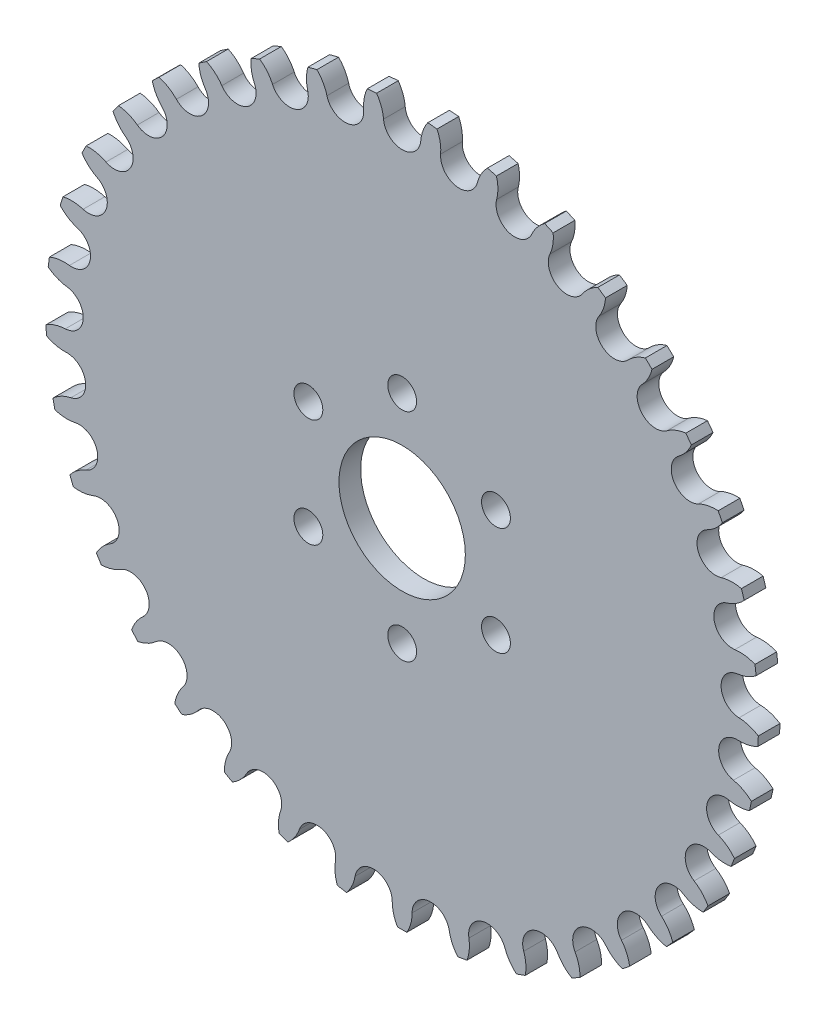
SolidWorks part; units mm, degrees
material "AISI 1020"
ref_plane "Спереди" through (0, 0, 0) normal (0, 0, 1) x (1, 0, 0)
ref_plane "Сверху" through (0, 0, 0) normal (0, 1, 0) x (1, 0, 0)
ref_plane "Справа" through (0, 0, 0) normal (1, 0, 0) x (0, 0, -1)
sketch "Эскиз1" plane through (0, 0, 0) normal (0, 0, 1) x (1, 0, 0)
  line L0 (0, 0) -> (0, 85) construction
  line L1 (0, 85) -> (15.8056, 83.5176) construction
  line L2 (15.8056, 83.5176) -> (0, 0) construction
  line L3 (15.8056, 83.5176) -> (49.3989, 83.5176)
  line L4 (0, 0) -> (0, 93.5961)
  line L5 (0, 93.5961) -> (15.8178, 92.2498)
  line L6 (15.8178, 92.2498) -> (0, 0)
  circle A0 centre (0, 0) radius 85 construction
  circle A1 centre (0, 93.5961) radius 5.08
  circle A2 centre (15.8178, 92.2498) radius 5.08
  dimension "D1" = 170
  dimension "D6" = 10.16
  dimension "D2" = 15.875
  dimension "D3" = 10.716
  dimension "D4" = 33.5932
  dimension "D5" = 9.73
sketch "Эскиз2" plane through (0, 0, 0) normal (0, 0, 1) x (1, 0, 0)
  line L0 (0, 0) -> (0, 88.4161)
  line L1 (0, 0) -> (14.9424, 87.1443)
  line L4 (15.8178, 92.2498) -> (0, 0) construction
  arc A0 (10.6565, 92.6891) -> (9.652, 98.2029) centre (0, 93.5961) ccw
  arc A1 (0, 98.6761) -> (16.6763, 97.2567) centre (0, 0) cw construction
  circle A2 centre (0, 93.5961) radius 5.08 construction
  circle A3 centre (15.8178, 92.2498) radius 5.08 construction
  circle A4 centre (0, 0) radius 85 construction
  circle A5 centre (0, 93.5961) radius 5.18
  arc A6 (0, 88.4161) -> (5.1613, 93.1568) centre (0, 93.5961) ccw
  arc A7 (7.0832, 98.4215) -> (5.1613, 93.1568) centre (15.8178, 92.2498) ccw
  circle A8 centre (15.8178, 92.2498) radius 5.18
  arc A9 (10.6565, 92.6891) -> (14.9424, 87.1443) centre (15.8178, 92.2498) ccw
  arc A10 (7.0832, 98.4215) -> (9.652, 98.2029) centre (0, 0) cw
  dimension "D1" = 0.1
  dimension "D2" = 0.1
extrude "Бобышка-Вытянуть1" add sketch "Эскиз2" along normal blind 6
pattern_circular "Круговой массив1" count 37 over 360 about axis through (0, 0, 0) along (0, 0, 1) of "Бобышка-Вытянуть1"
sketch "Эскиз3" plane through (0, 0, 6) normal (0, 0, 1) x (1, 0, 0)
  line L0 (0, 0) -> (0, 30) construction
  line L1 (0, 0) -> (25.9808, 15) construction
  circle A0 centre (0, 0) radius 17.5
  circle A1 centre (0, 0) radius 30 construction
  circle A2 centre (0, 30) radius 4
  circle A3 centre (25.9808, 15) radius 4
  circle A4 centre (25.9808, -15) radius 4
  circle A5 centre (0, -30) radius 4
  circle A6 centre (-25.9808, -15) radius 4
  circle A7 centre (-25.9808, 15) radius 4
  dimension "D1" = 35
  dimension "D2" = 60
  dimension "D3" = 8
  dimension "D5" = 60
  dimension "D6" = 30
  dimension "D4" = 6
extrude "Вырез-Вытянуть1" cut sketch "Эскиз3" against normal through all
equation "\"D4@Эскиз1\"=360/\"D3@Эскиз1\""
equation "\"D5@Эскиз1\"=360/37"
